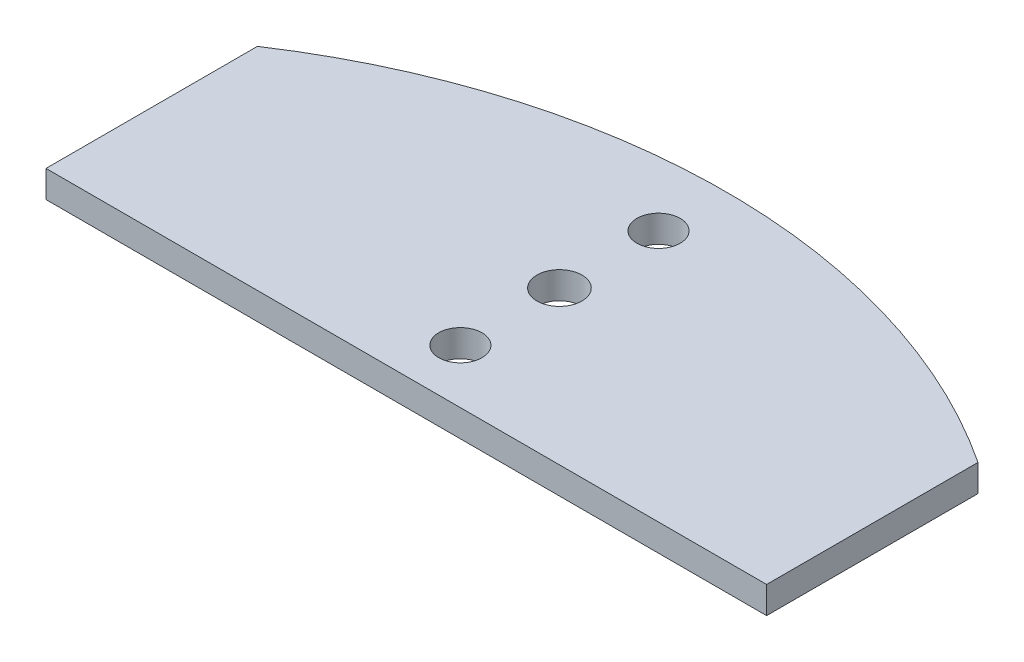
SolidWorks part; units mm, degrees
material "Acrylic (Medium-high impact)"
ref_plane "Front Plane" through (0, 0, 0) normal (0, 0, 1) x (1, 0, 0)
ref_plane "Top Plane" through (0, 0, 0) normal (0, 1, 0) x (1, 0, 0)
ref_plane "Right Plane" through (0, 0, 0) normal (1, 0, 0) x (0, 0, -1)
sketch "Sketch1" plane through (0, 0, 0) normal (0, 1, 0) x (1, 0, 0)
  line L0 (0, -85) -> (-32.4891, -64.8129) construction
  line L1 (0, -85) -> (0, 0) construction
  arc A0 (36.5434, -62.6165) -> (-36.5434, -62.6165) centre (0, 0) ccw
  arc A1 (30.0898, -61.3851) -> (-30.0898, -61.3851) centre (0, -85) ccw
  arc A2 (-30.0898, -61.3851) -> (-36.5434, -62.6165) centre (-34.0231, -58.2982) cw
  arc A3 (36.5434, -62.6165) -> (30.0898, -61.3851) centre (34.0231, -58.2982) cw
  dimension "D1" = 145
  dimension "D2" = 76.5
  dimension "D4" = 5
  dimension "D3" = 85
extrude "Boss-Extrude1" add sketch "Sketch1" along normal blind 3
sketch "Sketch11" plane through (0, 0, 0) normal (0, -1, 0) x (1, 0, 0)
  line L1 (40, -37) -> (-40, -37)
  line L2 (40, -37) -> (40, -77)
  line L3 (40, -77) -> (-40, -77)
  line L4 (-40, -37) -> (-40, -77)
  line L5 (40, -37) -> (-40, -77) construction
  line L6 (40, -77) -> (-40, -37) construction
  arc A0 (7.8724, -66.4231) -> (-7.8724, -66.4231) centre (0, -65) ccw construction
  point P0 (0, -57)
  dimension "D1" = 80
  dimension "D2" = 40
extrude "Cut-Extrude13" cut sketch "Sketch11" against normal through all flip side to cut
sketch "Sketch12" plane through (0, 0, 0) normal (0, -1, 0) x (1, 0, 0)
  circle A0 centre (0, -65) radius 2.4
  circle A1 centre (0, -43) radius 2.4
  dimension "D1" = 4.8
  dimension "D2" = 22
extrude "Cut-Extrude15" cut sketch "Sketch12" against normal through all
sketch "Sketch13" plane through (0, 0, 0) normal (0, -1, 0) x (1, 0, 0)
  line L0 (0, -65) -> (0, -43) construction
  circle A0 centre (0, -54) radius 2.5
  dimension "D1" = 5
extrude "Cut-Extrude16" cut sketch "Sketch13" against normal through all
equation "\"smallPulleyTeeth\"= 30"
equation "\"largePulleyTeeth\"= 30"
equation "\"eighthThick\"= 3.0mm"
equation "\"sixteenthThick\" = 1.7mm"
equation "\"quarterThick\"=6.0mm"
equation "\"OD\" = 145mm"
equation "\"puckAngle\" = 60.5deg"
equation "\"D1@Sketch1\"=\"OD\""
equation "\"puckDiam\" = 76.5mm"
equation "\"D2@Sketch1\"=\"puckDiam\""
equation "\"D1@Boss-Extrude1\"=\"eighthThick\""
equation "\"axlePress\" = 5.9mm"
equation "\"press\" = 0.2mm"
equation "\"wheelClear\" = 0.3mm"
equation "\"10-32clear\" = 4.8mm"
equation "\"6-32clear\" = 3.3mm"
equation "\"8-32clear\" = 4.0mm"
equation "\"wheelHeight\" = 22mm"
equation "\"wheelWell\" = 65mm"
equation "\"D1@Sketch3\"=\"wheelWell\""
equation "\"puckDist\" = 85mm"
equation "\"scoopFillet\" = 5mm"
equation "\"4-40clear\" = 3.0mm"
equation "\"D3@Sketch1\"=\"puckDist\""
equation "\"D4@Sketch1\"=\"scoopFillet\""
equation "\"D3@Sketch9\"=\"6-32clear\""
equation "\"D1@Sketch12\"=\"10-32clear\""
